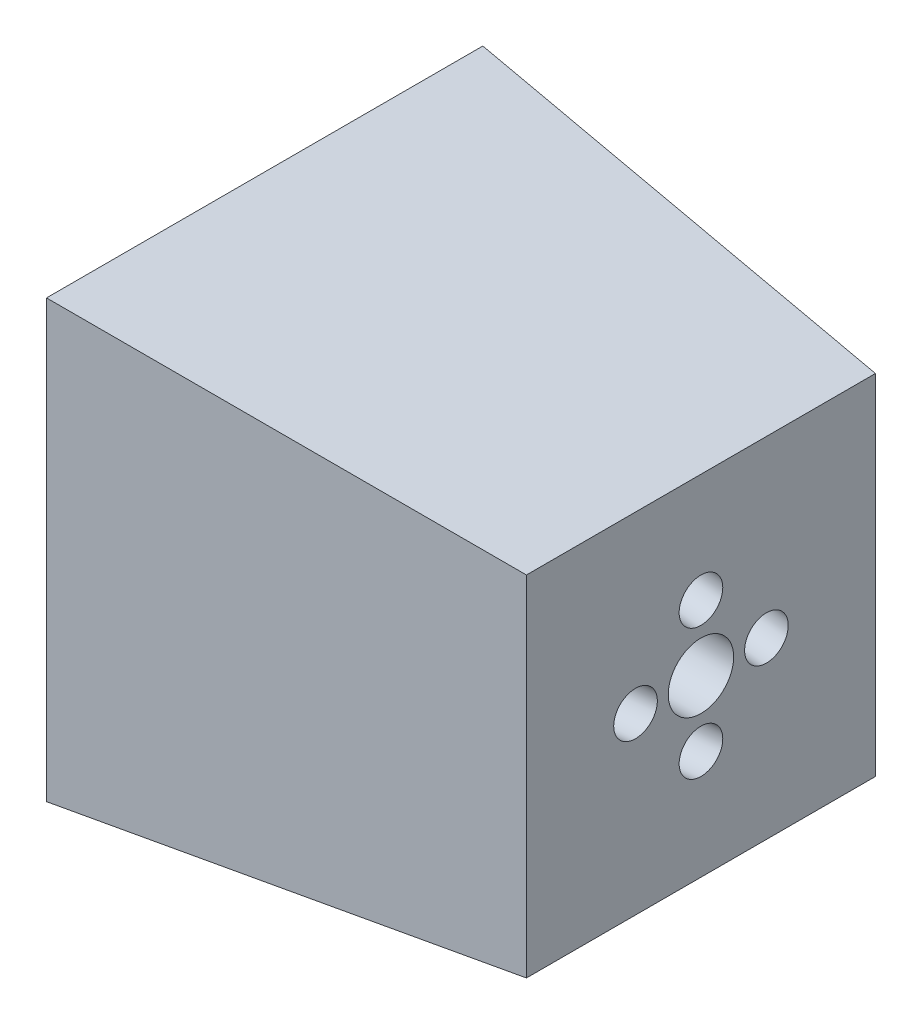
SolidWorks part; units mm, degrees
material "Silicon Rubber"
ref_plane "Front Plane" through (0, 0, 0) normal (0, 0, 1) x (1, 0, 0)
ref_plane "Top Plane" through (0, 0, 0) normal (0, 1, 0) x (1, 0, 0)
ref_plane "Right Plane" through (0, 0, 0) normal (1, 0, 0) x (0, 0, -1)
sketch "Sketch1" plane through (0, 0, 0) normal (1, 0, 0) x (0, 0, -1)
  line L1 (40, 40) -> (-40, 40)
  line L2 (40, 40) -> (40, -40)
  line L3 (40, -40) -> (-40, -40)
  line L4 (-40, 40) -> (-40, -40)
  line L5 (40, 40) -> (-40, -40) construction
  line L6 (40, -40) -> (-40, 40) construction
  point P0 (0, 0)
  dimension "D1" = 80
ref_plane "Plane1" through (-100, 0, 0) normal (1, 0, 0) x (0, 0, -1)
sketch "Sketch2" plane through (-100, 0, 0) normal (1, 0, 0) x (0, 0, -1)
  line L1 (50, 50) -> (-50, 50)
  line L2 (50, 50) -> (50, -50)
  line L3 (50, -50) -> (-50, -50)
  line L4 (-50, 50) -> (-50, -50)
  line L5 (50, 50) -> (-50, -50) construction
  line L6 (50, -50) -> (-50, 50) construction
  point P0 (0, 0)
  dimension "D1" = 100
loft "Loft1" add profiles "Sketch1", "Sketch2"
sketch "Sketch3" plane through (0, 0, 0) normal (1, 0, 0) x (0, 0, -1)
  circle A0 centre (15, 0) radius 5
  circle A1 centre (0, -15) radius 5 construction
  circle A2 centre (-15, 0) radius 5 construction
  circle A3 centre (0, 15) radius 5 construction
  point P12 (0, 0)
  dimension "D1" = 10
  dimension "D2" = 15
  dimension "D3" = 4
sketch "Sketch4" plane through (0, 0, 0) normal (0, 1, 0) x (1, 0, 0)
  line L0 (0, 15) -> (-100, 25)
  line L1 (0, 10) -> (0, 20) construction
  line L2 (-100, 50) -> (-100, -50) construction
  line L3 (0, 40) -> (-100, 50) construction
  line L5 (0, 0) -> (-133.0226, 0) construction
  line L6 (0, -15) -> (-100, -25)
sketch "Sketch5" plane through (0, 0, 0) normal (0, 0, 1) x (1, 0, 0)
  line L0 (0, 15) -> (-100, 25)
  line L1 (0, 10) -> (0, 20) construction
  line L2 (-100, 50) -> (-100, -50) construction
  line L3 (0, 40) -> (-100, 50) construction
  line L4 (0, 0) -> (34.2438, 0) construction
  line L5 (0, -15) -> (-100, -25)
sweep "Cut-Sweep2" cut profiles "Sketch3" path "Sketch4"
sketch "Sketch6" plane through (0, 0, 0) normal (1, 0, 0) x (0, 0, -1)
  circle A0 centre (0, 15) radius 5 construction
  circle A1 centre (15, 0) radius 5
  circle A2 centre (15, 0) radius 5 construction
  circle A3 centre (0, 15) radius 5
  dimension "D1" = 0
sweep "Cut-Sweep3" cut profiles "Sketch6" path "Sketch5"
mirror "Mirror1" about plane through (0, 0, 0) normal (0, 0, 1) of "Cut-Sweep2"
mirror "Mirror2" about plane through (0, 0, 0) normal (0, 1, 0) of "Cut-Sweep3"
sketch "Sketch7" plane through (0, 0, 0) normal (1, 0, 0) x (0, 0, -1)
  circle A0 centre (0, 0) radius 7.5
  dimension "D1" = 15
extrude "Cut-Extrude1" cut sketch "Sketch7" against normal through all
